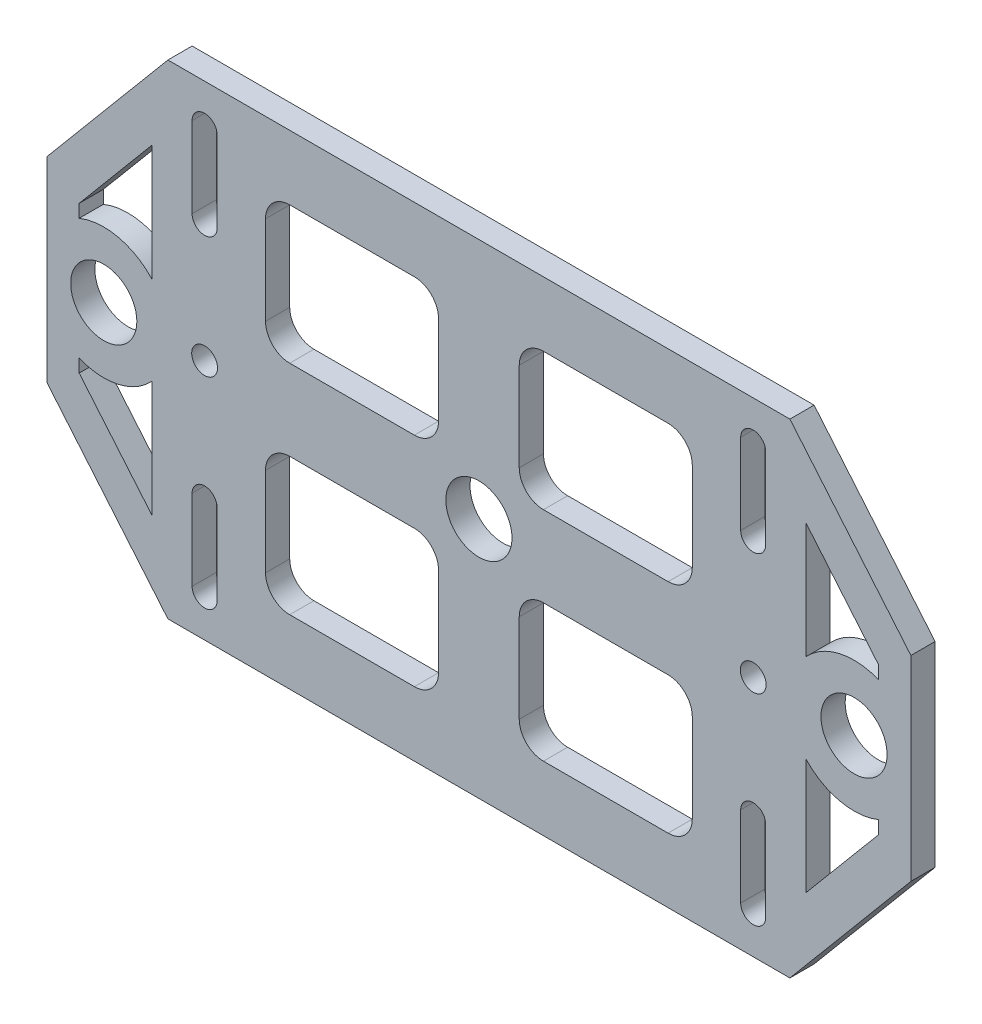
SolidWorks part; units mm, degrees
material "Thornel Mat VMA"
ref_plane "前视基准面" through (0, 0, 0) normal (0, 0, 1) x (1, 0, 0)
ref_plane "上视基准面" through (0, 0, 0) normal (0, 1, 0) x (1, 0, 0)
ref_plane "右视基准面" through (0, 0, 0) normal (1, 0, 0) x (0, 0, -1)
sketch "草图1" plane through (0, 0, 0) normal (0, 0, 1) x (1, 0, 0)
  line L0 (0, 25.3348) -> (0, -24.5642) construction
  line L1 (-32.3964, 0) -> (31.6755, 0) construction
  line L2 (35.55, -25) -> (32.45, -25)
  line L3 (-38.55, -30) -> (38.55, -30)
  line L4 (-38.55, -30) -> (-38.55, 30)
  line L5 (-38.55, 30) -> (38.55, 30)
  line L6 (38.55, -30) -> (38.55, 30)
  line L7 (-38.55, -30) -> (38.55, 30) construction
  line L8 (-38.55, 30) -> (38.55, -30) construction
  line L9 (-35.55, 25) -> (-32.45, 25)
  line L10 (-35.55, 25) -> (-35.55, 15)
  line L11 (-35.55, 15) -> (-32.45, 15)
  line L12 (-32.45, 25) -> (-32.45, 15)
  line L13 (-35.55, -15) -> (-32.45, -15)
  line L14 (-35.55, -15) -> (-35.55, -25)
  line L15 (-35.55, -25) -> (-32.45, -25)
  line L16 (-32.45, -15) -> (-32.45, -25)
  line L17 (32.45, -15) -> (32.45, -25)
  line L18 (35.55, -15) -> (32.45, -15)
  line L19 (35.55, -15) -> (35.55, -25)
  line L20 (35.55, 15) -> (32.45, 15)
  line L21 (32.45, 25) -> (32.45, 15)
  line L22 (35.55, 25) -> (32.45, 25)
  line L23 (35.55, 25) -> (35.55, 15)
  line L24 (34, -15) -> (34, 15) construction
  circle A0 centre (0, 0) radius 4.1
  circle A1 centre (34, 0) radius 1.6
  circle A2 centre (-34, 0) radius 1.6
  point P5 (0, 0)
  point P22 (-32.45, -20)
  point P23 (-32.45, 20)
  point P25 (-34, 15)
  dimension "D7" = 8.2
  dimension "D8" = 3.2
  dimension "D1" = 3
  dimension "D2" = 3.1
  dimension "D3" = 10
  dimension "D4" = 40
  dimension "D5" = 68
  dimension "D6" = 5
extrude "凸台-拉伸1" add sketch "草图1" along normal blind 3
sketch "草图2" plane through (0, 0, 3) normal (0, 0, 1) x (1, 0, 0)
  line L0 (-32.45, 25) -> (-35.55, 25) construction
  line L1 (-35.55, 15) -> (-32.45, 15) construction
  line L2 (35.55, 25) -> (32.45, 25) construction
  line L3 (32.45, 15) -> (35.55, 15) construction
  line L4 (35.55, -15) -> (32.45, -15) construction
  line L5 (32.45, -25) -> (35.55, -25) construction
  line L6 (-32.45, -15) -> (-35.55, -15) construction
  line L7 (-35.55, -25) -> (-32.45, -25) construction
  line L8 (0, 30) -> (0, -30) construction
  line L9 (38.55, 30) -> (-38.55, 30) construction
  line L10 (-38.55, -30) -> (38.55, -30) construction
  line L11 (-38.55, 0) -> (38.55, 0) construction
  line L12 (-38.55, 30) -> (-38.55, -30) construction
  line L13 (38.55, -30) -> (38.55, 30) construction
  line L14 (-32.45, -25) -> (-32.45, -15) construction
  line L15 (-26.45, 22) -> (-5, 22)
  line L16 (-26.45, 22) -> (-26.45, 5)
  line L17 (-26.45, 5) -> (-5, 5)
  line L18 (26.45, 22) -> (26.45, 5)
  line L19 (-26.45, 22) -> (26.45, 5) construction
  line L20 (-26.45, 5) -> (26.45, 22) construction
  line L21 (-26.45, -5) -> (-5, -5)
  line L22 (-26.45, -5) -> (-26.45, -22)
  line L23 (-26.45, -22) -> (-5, -22)
  line L24 (26.45, -5) -> (26.45, -22)
  line L25 (-26.45, -5) -> (26.45, -22) construction
  line L26 (-26.45, -22) -> (26.45, -5) construction
  line L27 (-5, 22) -> (-5, 5)
  line L28 (5, 22) -> (5, 5)
  line L29 (-5, -5) -> (-5, -22)
  line L30 (5, -5) -> (5, -22)
  line L31 (5, 22) -> (26.45, 22)
  line L32 (5, 5) -> (26.45, 5)
  line L33 (5, -5) -> (26.45, -5)
  line L34 (5, -22) -> (26.45, -22)
  circle A0 centre (-34, 25) radius 1.55
  circle A1 centre (-34, 15) radius 1.55
  circle A2 centre (34, 25) radius 1.55
  circle A3 centre (34, 15) radius 1.55
  circle A4 centre (34, -15) radius 1.55
  circle A5 centre (34, -25) radius 1.55
  circle A6 centre (-34, -15) radius 1.55
  circle A7 centre (-34, -25) radius 1.55
  circle A8 centre (0, 0) radius 4.1 construction
  point P52 (0, 13.5)
  point P57 (0, -13.5)
  dimension "D1" = 5
  dimension "D2" = 8
  dimension "D3" = 6
  dimension "D4" = 10
extrude "切除-拉伸1" cut sketch "草图2" against normal through all
sketch "草图3" plane through (0, 0, 3) normal (0, 0, 1) x (1, 0, 0)
  line L0 (-53.1008, 0) -> (55.5621, 0) construction
  line L1 (0, 37.8516) -> (0, -36.2897) construction
  line L2 (-38.55, 30) -> (-53.55, 12.1237)
  line L3 (-53.55, 12.1237) -> (-53.55, -12.1237)
  line L4 (-53.55, -12.1237) -> (-38.55, -30)
  line L5 (-38.55, -30) -> (-38.55, 30)
  line L6 (-40.55, 19.8379) -> (-49.55, 9.1121)
  line L7 (-49.55, 9.1121) -> (-49.55, 7.5038)
  line L8 (-40.55, 19.8379) -> (-40.55, 5.4961)
  line L9 (-49.55, -7.5038) -> (-49.55, -9.1121)
  line L10 (-49.55, -9.1121) -> (-40.55, -19.8379)
  line L11 (-40.55, -19.8379) -> (-40.55, -5.4961)
  line L12 (40.55, -19.8379) -> (40.55, -5.4961)
  line L13 (49.55, -9.1121) -> (40.55, -19.8379)
  line L14 (49.55, -7.5038) -> (49.55, -9.1121)
  line L15 (53.55, -12.1237) -> (38.55, -30)
  line L16 (53.55, 12.1237) -> (53.55, -12.1237)
  line L17 (38.55, 30) -> (53.55, 12.1237)
  line L18 (38.55, -30) -> (38.55, 30)
  line L19 (40.55, 19.8379) -> (49.55, 9.1121)
  line L20 (40.55, 19.8379) -> (40.55, 5.4961)
  line L21 (49.55, 9.1121) -> (49.55, 7.5038)
  circle A0 centre (-46.5, 0) radius 4.1
  arc A1 (-49.55, -7.5038) -> (-40.55, -5.4961) centre (-46.5, 0) ccw
  arc A2 (49.55, -7.5038) -> (40.55, -5.4961) centre (46.5, 0) cw
  arc A3 (-40.55, 5.4961) -> (-49.55, 7.5038) centre (-46.5, 0) ccw
  circle A4 centre (46.5, 0) radius 4.1
  arc A5 (40.55, 5.4961) -> (49.55, 7.5038) centre (46.5, 0) cw
  circle A6 centre (0, 0) radius 4.1 construction
  dimension "D2" = 8.2
  dimension "D3" = 46.5
  dimension "D5" = 5
  dimension "D8" = 4
  dimension "D1" = 15
  dimension "D4" = 40
  dimension "D6" = 2
  dimension "D7" = 4
extrude "凸台-拉伸2" add sketch "草图3" against normal up to surface (3 mm away) up to face at (34, -20, 0)
fillet "圆角1" radius 3 16 edges at (26.45, 22, 1.5) (5, 22, 1.5) (5, 5, 1.5) (26.45, 5, 1.5) (26.45, -22, 1.5) (26.45, -5, 1.5) (5, -5, 1.5) (5, -22, 1.5) (-26.45, -22, 1.5) (-26.45, -5, 1.5) (-5, -22, 1.5) (-5, -5, 1.5) (-5, 5, 1.5) (-26.45, 5, 1.5) (-5, 22, 1.5) (-26.45, 22, 1.5)
